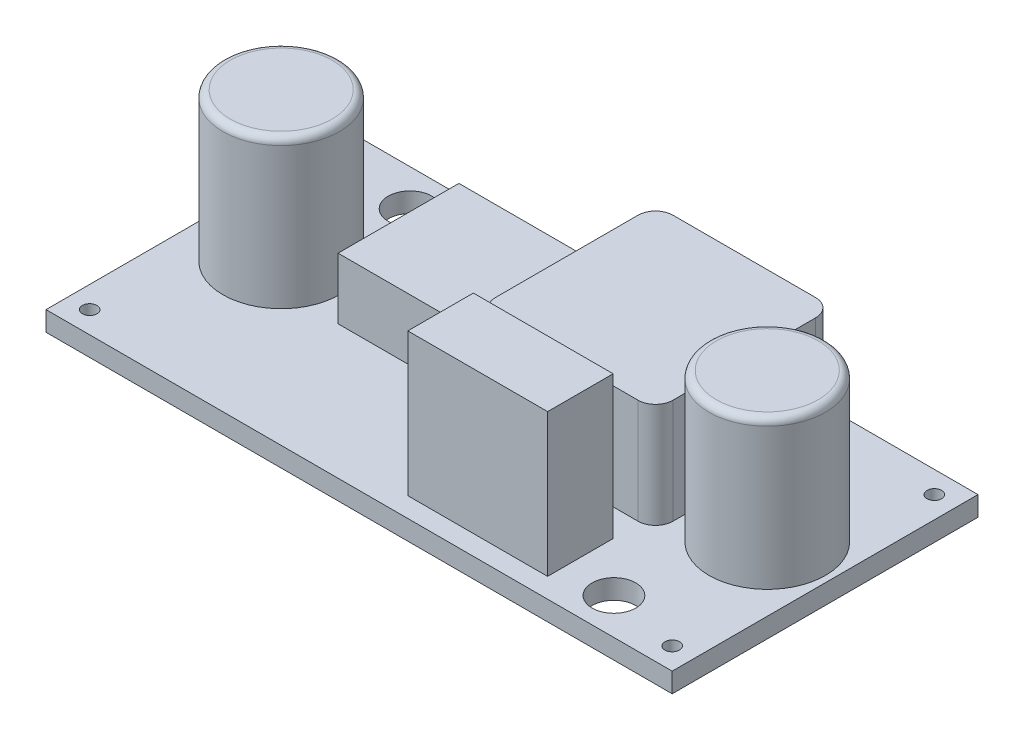
SolidWorks part; units mm, degrees
ref_plane "Front Plane" through (0, 0, 0) normal (0, 0, 1) x (1, 0, 0)
ref_plane "Top Plane" through (0, 0, 0) normal (0, 1, 0) x (1, 0, 0)
ref_plane "Right Plane" through (0, 0, 0) normal (1, 0, 0) x (0, 0, -1)
sketch "Sketch2" plane through (0, 0, 0) normal (0, 1, 0) x (1, 0, 0)
  line L1 (-21.5, -10.5) -> (21.5, -10.5)
  line L2 (-21.5, -10.5) -> (-21.5, 10.5)
  line L3 (-21.5, 10.5) -> (21.5, 10.5)
  line L4 (21.5, -10.5) -> (21.5, 10.5)
  circle A0 centre (-15, 8) radius 1.5
  circle A2 centre (15, -8) radius 1.5
  point P0 (0, 0)
  dimension "D3" = 3
  dimension "D4" = 6.5
  dimension "D5" = 2.5
  dimension "D1" = 43
  dimension "D2" = 21
extrude "Boss-Extrude1" add sketch "Sketch2" along normal blind 1.35
sketch "Sketch3" plane through (0, 1.35, 0) normal (0, 1, 0) x (1, 0, 0)
  line L0 (-21.5, 10.5) -> (-21.5, -10.5) construction
  line L1 (21.5, 10.5) -> (-21.5, 10.5) construction
  circle A0 centre (-20, 9) radius 0.5
  circle A1 centre (20, 9) radius 0.5
  circle A2 centre (-20, -9) radius 0.5
  circle A3 centre (20, -9) radius 0.5
  dimension "D1" = 1
  dimension "D2" = 1.5
  dimension "D3" = 1.5
extrude "Cut-Extrude1" cut sketch "Sketch3" against normal through all
sketch "Sketch4" plane through (0, 1.35, 0) normal (0, 1, 0) x (1, 0, 0)
  line L0 (1.6129, 9.4415) -> (11.4129, 9.4415)
  line L1 (0.4129, 8.2415) -> (0.4129, -1.5585)
  line L2 (1.6129, -2.7585) -> (11.4129, -2.7585)
  line L3 (12.6129, 8.2415) -> (12.6129, -1.5585)
  line L8 (-10.4827, 0.5243) -> (-0.9827, 0.5243)
  line L9 (-10.4827, 0.5243) -> (-10.4827, 8.8243)
  line L10 (-10.4827, 8.8243) -> (-0.9827, 8.8243)
  line L11 (-0.9827, 0.5243) -> (-0.9827, 8.8243)
  arc A0 (11.4129, 9.4415) -> (12.6129, 8.2415) centre (11.4129, 8.2415) cw
  arc A1 (11.4129, -2.7585) -> (12.6129, -1.5585) centre (11.4129, -1.5585) ccw
  arc A2 (0.4129, -1.5585) -> (1.6129, -2.7585) centre (1.6129, -1.5585) ccw
  arc A3 (1.6129, 9.4415) -> (0.4129, 8.2415) centre (1.6129, 8.2415) ccw
extrude "Boss-Extrude2" add sketch "Sketch4" along normal blind 7.2 separate body contours L0 A0 L3 A1 L2 A2 L1 A3
sketch "Sketch6" plane through (0, 1.35, 0) normal (0, 1, 0) x (1, 0, 0)
  line L0 (1.9879, -4.6429) -> (11.5879, -4.6429)
  line L1 (1.9879, -4.6429) -> (1.9879, -9.1429)
  line L2 (1.9879, -9.1429) -> (11.5879, -9.1429)
  line L3 (11.5879, -4.6429) -> (11.5879, -9.1429)
extrude "Boss-Extrude3" add sketch "Sketch6" along normal blind 9.8 separate body contours L0 L3 L2 L1
sketch "Sketch7" plane through (0, 1.35, 0) normal (0, 1, 0) x (1, 0, 0)
  line L0 (-10.6282, -1.3159) -> (-1.1282, -1.3159)
  line L1 (-10.6282, -1.3159) -> (-10.6282, 6.9841)
  line L2 (-10.6282, 6.9841) -> (-1.1282, 6.9841)
  line L3 (-1.1282, -1.3159) -> (-1.1282, 6.9841)
extrude "Boss-Extrude4" add sketch "Sketch7" along normal blind 4.2 separate body
sketch "Sketch8" plane through (0, 1.35, 0) normal (0, 1, 0) x (1, 0, 0)
  circle A0 centre (-16.305, 0.4549) radius 4
  circle A1 centre (17.0748, 0.4549) radius 4
  dimension "D1" = 8
  dimension "D2" = 8
extrude "Boss-Extrude5" add sketch "Sketch8" along normal blind 10.2 separate body
fillet "Fillet1" radius 0.5 1 edges at (-16.305, 11.55, 3.5451)
fillet "Fillet2" radius 0.5 1 edges at (17.0748, 11.55, 3.5451)
